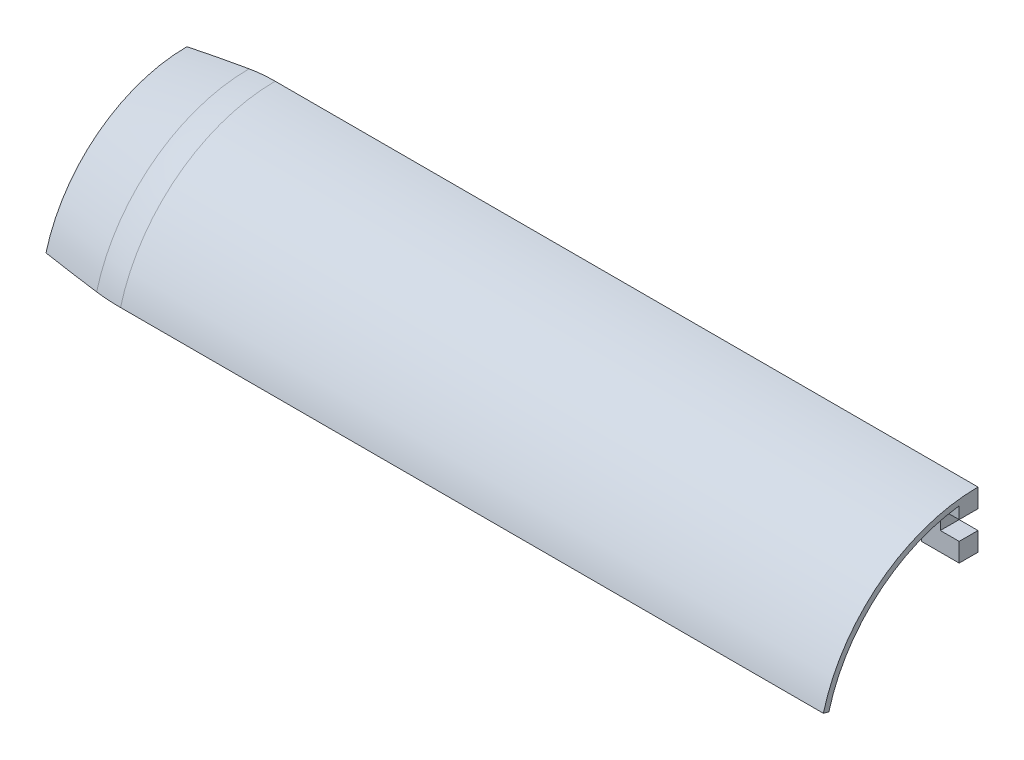
SolidWorks part; units mm, degrees
ref_plane "Front Plane" through (0, 0, 0) normal (0, 0, 1) x (1, 0, 0)
ref_plane "Top Plane" through (0, 0, 0) normal (0, 1, 0) x (1, 0, 0)
ref_plane "Right Plane" through (0, 0, 0) normal (1, 0, 0) x (0, 0, -1)
curve "Curve1"
  spline degree 3 poles (0, 0, 0) (-0.0123, 3.8916, 0) (-0.0274, 8.685, 0) (0.3616, 14.0857, 0) (0.5761, 16.0905, 0) (0.7825, 17.6048, 0) (0.9862, 18.8543, 0) (1.1887, 19.9315, 0) (1.3904, 20.8857, 0) (1.5917, 21.7465, 0) (1.7927, 22.5337, 0) (1.9935, 23.2611, 0) (2.1942, 23.9386, 0) (2.3947, 24.5739, 0) (2.5952, 25.1728, 0) (2.7956, 25.7401, 0) (2.9959, 26.2796, 0) (3.1962, 26.7943, 0) (3.3965, 27.2868, 0) (3.5967, 27.7594, 0) (3.7969, 28.2139, 0) (3.9971, 28.6519, 0) (4.1973, 29.0748, 0) (4.3974, 29.4838, 0) (4.5976, 29.8799, 0) (4.7977, 30.2641, 0) (4.9978, 30.6373, 0) (5.1979, 31.0001, 0) (5.398, 31.3533, 0) (5.5981, 31.6974, 0) (5.7982, 32.033, 0) (5.9983, 32.3606, 0) (6.1984, 32.6807, 0) (6.3985, 32.9935, 0) (6.5985, 33.2996, 0) (6.7986, 33.5993, 0) (6.9986, 33.8929, 0) (7.1987, 34.1806, 0) (7.3987, 34.4628, 0) (7.5988, 34.7397, 0) (7.7988, 35.0115, 0) (7.9989, 35.2785, 0) (8.1989, 35.5408, 0) (8.399, 35.7988, 0) (8.599, 36.0524, 0) (8.799, 36.3019, 0) (8.9991, 36.5476, 0) (9.1991, 36.7894, 0) (9.3991, 37.0275, 0) (9.5992, 37.2622, 0) (9.7992, 37.4934, 0) (9.9992, 37.7214, 0) (10.1992, 37.9461, 0) (10.3993, 38.1679, 0) (10.5993, 38.3866, 0) (10.7993, 38.6025, 0) (10.9993, 38.8156, 0) (11.1993, 39.026, 0) (11.3994, 39.2338, 0) (11.5994, 39.4391, 0) (11.7994, 39.6419, 0) (11.9994, 39.8422, 0) (12.1994, 40.0403, 0) (12.3995, 40.2361, 0) (12.5995, 40.4297, 0) (12.7995, 40.6212, 0) (12.9995, 40.8106, 0) (13.1995, 40.998, 0) (13.3995, 41.1834, 0) (13.5995, 41.3668, 0) (13.7995, 41.5484, 0) (13.9996, 41.7281, 0) (14.1996, 41.9061, 0) (14.3996, 42.0823, 0) (14.5996, 42.2568, 0) (14.7996, 42.4296, 0) (14.9996, 42.6008, 0) (15.1996, 42.7705, 0) (15.3996, 42.9385, 0) (15.5996, 43.1051, 0) (15.7996, 43.2701, 0) (15.9997, 43.4337, 0) (16.1997, 43.5959, 0) (16.3997, 43.7567, 0) (16.5997, 43.9161, 0) (16.7997, 44.0742, 0) (16.9997, 44.2309, 0) (17.1997, 44.3864, 0) (17.3997, 44.5406, 0) (17.5997, 44.6936, 0) (17.7997, 44.8453, 0) (17.9997, 44.9959, 0) (18.1997, 45.1453, 0) (18.3997, 45.2936, 0) (18.5997, 45.4407, 0) (18.7997, 45.5868, 0) (18.9997, 45.7317, 0) (19.1998, 45.8756, 0) (19.3998, 46.0185, 0) (19.5998, 46.1603, 0) (19.7998, 46.3011, 0) (19.9998, 46.4409, 0) (20.1998, 46.5797, 0) (20.3998, 46.7176, 0) (20.5998, 46.8546, 0) (20.7998, 46.9906, 0) (20.9998, 47.1257, 0) (21.1998, 47.2599, 0) (21.3998, 47.3932, 0) (21.5998, 47.5256, 0) (21.7998, 47.6572, 0) (21.9998, 47.788, 0) (22.1998, 47.9179, 0) (22.3998, 48.047, 0) (22.5998, 48.1753, 0) (22.7998, 48.3028, 0) (22.9998, 48.4295, 0) (23.1998, 48.5555, 0) (23.3998, 48.6807, 0) (23.5998, 48.8051, 0) (23.7998, 48.9288, 0) (23.9998, 49.0518, 0) (24.1998, 49.1741, 0) (24.3998, 49.2957, 0) (24.5998, 49.4165, 0) (24.7999, 49.5367, 0) (24.9999, 49.6562, 0) (25.1999, 49.7751, 0) (25.3999, 49.8933, 0) (25.5999, 50.0108, 0) (25.7999, 50.1277, 0) (25.9999, 50.2439, 0) (26.1999, 50.3596, 0) (26.3999, 50.4746, 0) (26.5999, 50.589, 0) (26.7999, 50.7028, 0) (26.9999, 50.8161, 0) (27.1999, 50.9287, 0) (27.3999, 51.0407, 0) (27.5999, 51.1522, 0) (27.7999, 51.2631, 0) (27.9999, 51.3735, 0) (28.1999, 51.4833, 0) (28.3999, 51.5926, 0) (28.5999, 51.7013, 0) (28.7999, 51.8095, 0) (28.9999, 51.9172, 0) (29.1999, 52.0243, 0) (29.3999, 52.131, 0) (29.5999, 52.2371, 0) (29.7999, 52.3428, 0) (29.9999, 52.4479, 0) (30.1999, 52.5526, 0) (30.3999, 52.6567, 0) (30.5999, 52.7604, 0) (30.7999, 52.8636, 0) (30.9999, 52.9664, 0) (31.1999, 53.0687, 0) (31.3999, 53.1705, 0) (31.5999, 53.2719, 0) (31.7999, 53.3728, 0) (31.9999, 53.4733, 0) (32.1999, 53.5733, 0) (32.3999, 53.6729, 0) (32.5999, 53.7721, 0) (32.7999, 53.8709, 0) (32.9999, 53.9692, 0) (33.1999, 54.0671, 0) (33.3999, 54.1646, 0) (33.5999, 54.2617, 0) (33.7999, 54.3584, 0) (33.9999, 54.4547, 0) (34.1999, 54.5506, 0) (34.3999, 54.6461, 0) (34.5999, 54.7412, 0) (34.7999, 54.836, 0) (34.9999, 54.9303, 0) (35.1999, 55.0243, 0) (35.3999, 55.1179, 0) (35.5999, 55.2111, 0) (35.7999, 55.304, 0) (35.9999, 55.3965, 0) (36.1999, 55.4887, 0) (36.3999, 55.5805, 0) (36.5999, 55.6719, 0) (36.7999, 55.763, 0) (36.9999, 55.8537, 0) (37.1999, 55.9441, 0) (37.3999, 56.0342, 0) (37.5999, 56.1239, 0) (37.7999, 56.2133, 0) (37.9999, 56.3024, 0) (38.1999, 56.3911, 0) (38.3999, 56.4795, 0) (38.5999, 56.5676, 0) (38.7999, 56.6554, 0) (38.9999, 56.7428, 0) (39.1999, 56.83, 0) (39.3999, 56.9168, 0) (39.5999, 57.0033, 0) (39.7999, 57.0896, 0) (39.9999, 57.1755, 0) (40.1999, 57.2611, 0) (40.3999, 57.3464, 0) (40.5999, 57.4314, 0) (40.7999, 57.5161, 0) (40.9999, 57.6006, 0) (41.1999, 57.6847, 0) (41.3999, 57.7686, 0) (41.6, 57.8522, 0) (41.8, 57.9355, 0) (42, 58.0185, 0) (42.2, 58.1012, 0) (42.4, 58.1837, 0) (42.6, 58.2659, 0) (42.8, 58.3479, 0) (43, 58.4295, 0) (43.2, 58.5109, 0) (43.4, 58.592, 0) (43.6, 58.6729, 0) (43.8, 58.7535, 0) (44, 58.8339, 0) (44.2, 58.914, 0) (44.4, 58.9938, 0) (44.6, 59.0734, 0) (44.8, 59.1528, 0) (45, 59.2319, 0) (45.2, 59.3107, 0) (45.4, 59.3893, 0) (45.6, 59.4677, 0) (45.8, 59.5458, 0) (46, 59.6237, 0) (46.2, 59.7014, 0) (46.4, 59.7788, 0) (46.6, 59.856, 0) (46.8, 59.9329, 0) (47, 60.0096, 0) (47.2, 60.0861, 0) (47.4, 60.1624, 0) (47.6, 60.2385, 0) (47.8, 60.3143, 0) (48, 60.3899, 0) (48.2, 60.4652, 0) (48.4, 60.5404, 0) (48.6, 60.6153, 0) (48.8, 60.6901, 0) (49, 60.7646, 0) (49.2, 60.8389, 0) (49.4, 60.913, 0) (49.6, 60.9869, 0) (49.8, 61.0605, 0) (50, 61.134, 0) (50.2, 61.2072, 0) (50.4, 61.2803, 0) (50.6, 61.3531, 0) (50.8, 61.4258, 0) (51, 61.4982, 0) (51.2, 61.5705, 0) (51.4, 61.6426, 0) (51.6, 61.7144, 0) (51.8, 61.7861, 0) (52, 61.8575, 0) (52.2, 61.9288, 0) (52.4, 61.9999, 0) (52.6, 62.0708, 0) (52.8, 62.1415, 0) (53, 62.212, 0) (53.2, 62.2824, 0) (53.4, 62.3525, 0) (53.6, 62.4225, 0) (53.8, 62.4923, 0) (54, 62.5619, 0) (54.2, 62.6313, 0) (54.4, 62.7006, 0) (54.6, 62.7696, 0) (54.8, 62.8385, 0) (55, 62.9072, 0) (55.2, 62.9758, 0) (55.4, 63.0441, 0) (55.6, 63.1123, 0) (55.8, 63.1803, 0) (56, 63.2482, 0) (56.2, 63.3159, 0) (56.4, 63.3834, 0) (56.6, 63.4507, 0) (56.8, 63.5179, 0) (57, 63.5849, 0) (57.2, 63.6518, 0) (57.4, 63.7185, 0) (57.6, 63.785, 0) (57.8, 63.8513, 0) (58, 63.9175, 0) (58.2, 63.9836, 0) (58.4, 64.0495, 0) (58.6, 64.1152, 0) (58.8, 64.1808, 0) (59, 64.2462, 0) (59.2, 64.3114, 0) (59.4, 64.3765, 0) (59.6, 64.4415, 0) (59.8, 64.5063, 0) (60, 64.5709, 0) (60.2, 64.6354, 0) (60.4, 64.6998, 0) (60.6, 64.764, 0) (60.8, 64.828, 0) (61, 64.8919, 0) (61.2, 64.9557, 0) (61.4, 65.0193, 0) (61.6, 65.0827, 0) (61.8, 65.1461, 0) (62, 65.2092, 0) (62.2, 65.2723, 0) (62.4, 65.3352, 0) (62.6, 65.3979, 0) (62.8, 65.4605, 0) (63, 65.523, 0) (63.2, 65.5853, 0) (63.4, 65.6475, 0) (63.6, 65.7096, 0) (63.8, 65.7715, 0) (64, 65.8333, 0) (64.2, 65.895, 0) (64.4, 65.9565, 0) (64.6, 66.0179, 0) (64.8, 66.0791, 0) (65, 66.1402, 0) (65.2, 66.2012, 0) (65.4, 66.2621, 0) (65.6, 66.3228, 0) (65.8, 66.3834, 0) (66, 66.4439, 0) (66.2, 66.5042, 0) (66.4, 66.5644, 0) (66.6, 66.6245, 0) (66.8, 66.6845, 0) (67, 66.7443, 0) (67.2, 66.804, 0) (67.4, 66.8636, 0) (67.6, 66.923, 0) (67.8, 66.9824, 0) (68, 67.0416, 0) (68.2, 67.1007, 0) (68.4, 67.1597, 0) (68.6, 67.2185, 0) (68.8, 67.2772, 0) (69, 67.3359, 0) (69.2, 67.3943, 0) (69.4, 67.4527, 0) (69.6, 67.511, 0) (69.8, 67.5691, 0) (70, 67.6271, 0) (70.2, 67.6851, 0) (70.4, 67.7428, 0) (70.6, 67.8005, 0) (70.8, 67.8581, 0) (71, 67.9155, 0) (71.2, 67.9729, 0) (71.4, 68.0301, 0) (71.6, 68.0872, 0) (71.8, 68.1442, 0) (72, 68.2011, 0) (72.2, 68.2579, 0) (72.4, 68.3145, 0) (72.6, 68.3711, 0) (72.8, 68.4276, 0) (73, 68.4839, 0) (73.2, 68.5401, 0) (73.4, 68.5963, 0) (73.6, 68.6523, 0) (73.8, 68.7082, 0) (74, 68.764, 0) (74.2, 68.8197, 0) (74.4, 68.8753, 0) (74.6, 68.9308, 0) (74.8, 68.9862, 0) (75, 69.0415, 0) (75.2, 69.0966, 0) (75.4, 69.1517, 0) (75.6, 69.2067, 0) (75.8, 69.2616, 0) (76, 69.3164, 0) (76.2, 69.371, 0) (76.4, 69.4256, 0) (76.6, 69.4801, 0) (76.8, 69.5344, 0) (77, 69.5887, 0) (77.2, 69.6429, 0) (77.4, 69.697, 0) (77.6, 69.751, 0) (77.8, 69.8048, 0) (78, 69.8586, 0) (78.2, 69.9123, 0) (78.4, 69.9659, 0) (78.6, 70.0194, 0) (78.8, 70.0728, 0) (79, 70.1261, 0) (79.2, 70.1793, 0) (79.4, 70.2324, 0) (79.6, 70.2855, 0) (79.8, 70.3384, 0) (80, 70.3912, 0) (80.2, 70.444, 0) (80.4, 70.4966, 0) (80.6, 70.5492, 0) (80.8, 70.6017, 0) (81, 70.6541, 0) (81.2, 70.7064, 0) (81.4, 70.7586, 0) (81.6, 70.8107, 0) (81.8, 70.8627, 0) (82, 70.9146, 0) (82.2, 70.9665, 0) (82.4, 71.0182, 0) (82.6, 71.0699, 0) (82.8, 71.1215, 0) (83, 71.173, 0) (83.2, 71.2244, 0) (83.4, 71.2757, 0) (83.6, 71.3269, 0) (83.8, 71.3781, 0) (84, 71.4291, 0) (84.2, 71.4801, 0) (84.4, 71.531, 0) (84.6, 71.5818, 0) (84.8, 71.6325, 0) (85, 71.6832, 0) (85.2, 71.7337, 0) (85.4, 71.7842, 0) (85.6, 71.8346, 0) (85.8, 71.8849, 0) (86, 71.9351, 0) (86.2, 71.9853, 0) (86.4, 72.0354, 0) (86.6, 72.0853, 0) (86.8, 72.1352, 0) (87, 72.1851, 0) (87.2, 72.2348, 0) (87.4, 72.2845, 0) (87.6, 72.3341, 0) (87.8, 72.3836, 0) (88, 72.433, 0) (88.2, 72.4823, 0) (88.4, 72.5316, 0) (88.6, 72.5808, 0) (88.8, 72.6299, 0) (89, 72.6789, 0) (89.2, 72.7279, 0) (89.4, 72.7768, 0) (89.6, 72.8256, 0) (89.8, 72.8743, 0) (90, 72.923, 0) (90.2, 72.9716, 0) (90.4, 73.0201, 0) (90.6, 73.0685, 0) (90.8, 73.1168, 0) (91, 73.1651, 0) (91.2, 73.2133, 0) (91.4, 73.2614, 0) (91.6, 73.3095, 0) (91.8, 73.3575, 0) (92, 73.4054, 0) (92.2, 73.4532, 0) (92.4, 73.501, 0) (92.6, 73.5487, 0) (92.8, 73.5963, 0) (93, 73.6439, 0) (93.2, 73.6913, 0) (93.4, 73.7387, 0) (93.6, 73.7861, 0) (93.8, 73.8333, 0) (94, 73.8805, 0) (94.2, 73.9276, 0) (94.4, 73.9747, 0) (94.6, 74.0217, 0) (94.8, 74.0686, 0) (95, 74.1154, 0) (95.2, 74.1622, 0) (95.4, 74.2089, 0) (95.6, 74.2556, 0) (95.8, 74.3021, 0) (96, 74.3486, 0) (96.2, 74.3951, 0) (96.4, 74.4414, 0) (96.6, 74.4877, 0) (96.8, 74.534, 0) (97, 74.5801, 0) (97.2, 74.6262, 0) (97.4, 74.6723, 0) (97.6, 74.7182, 0) (97.8, 74.7641, 0) (98, 74.81, 0) (98.2, 74.8557, 0) (98.4, 74.9014, 0) (98.6, 74.9471, 0) (98.8, 74.9926, 0) (99, 75.0382, 0) (99.2, 75.0836, 0) (99.4, 75.129, 0) (99.6, 75.1743, 0) (99.8, 75.2196, 0) (100, 75.2647, 0) (100.2, 75.3099, 0) (100.4, 75.3549, 0) (100.6, 75.3999, 0) (100.8, 75.4449, 0) (101, 75.4898, 0) (101.2, 75.5346, 0) (101.4, 75.5793, 0) (101.6, 75.624, 0) (101.8, 75.6686, 0) (102, 75.7132, 0) (102.2, 75.7577, 0) (102.4, 75.8022, 0) (102.6, 75.8465, 0) (102.8, 75.8909, 0) (103, 75.9351, 0) (103.2, 75.9793, 0) (103.4, 76.0235, 0) (103.6, 76.0676, 0) (103.8, 76.1116, 0) (104, 76.1556, 0) (104.2, 76.1995, 0) (104.4, 76.2433, 0) (104.6, 76.2871, 0) (104.8, 76.3308, 0) (105, 76.3745, 0) (105.2, 76.4181, 0) (105.4, 76.4617, 0) (105.6, 76.5052, 0) (105.8, 76.5486, 0) (106, 76.592, 0) (106.2, 76.6353, 0) (106.4, 76.6786, 0) (106.6, 76.7218, 0) (106.8, 76.7649, 0) (107, 76.808, 0) (107.2, 76.8511, 0) (107.4, 76.8941, 0) (107.6, 76.937, 0) (107.8, 76.9799, 0) (108, 77.0227, 0) (108.2, 77.0655, 0) (108.4, 77.1082, 0) (108.6, 77.1508, 0) (108.8, 77.1934, 0) (109, 77.236, 0) (109.2, 77.2784, 0) (109.4, 77.3209, 0) (109.6, 77.3633, 0) (109.8, 77.4056, 0) (110, 77.4479, 0) (110.2, 77.4901, 0) (110.4, 77.5322, 0) (110.6, 77.5743, 0) (110.8, 77.6164, 0) (111, 77.6584, 0) (111.2, 77.7004, 0) (111.4, 77.7423, 0) (111.6, 77.7841, 0) (111.8, 77.8259, 0) (112, 77.8676, 0) (112.2, 77.9093, 0) (112.4, 77.951, 0) (112.6, 77.9925, 0) (112.8, 78.0341, 0) (113, 78.0756, 0) (113.2, 78.117, 0) (113.4, 78.1584, 0) (113.6, 78.1997, 0) (113.8, 78.241, 0) (114, 78.2822, 0) (114.2, 78.3234, 0) (114.4, 78.3645, 0) (114.6, 78.4056, 0) (114.8, 78.4466, 0) (115, 78.4876, 0) (115.2, 78.5285, 0) (115.4, 78.5694, 0) (115.6, 78.6102, 0) (115.8, 78.651, 0) (116, 78.6917, 0) (116.2, 78.7324, 0) (116.4, 78.773, 0) (116.6, 78.8136, 0) (116.8, 78.8541, 0) (117, 78.8946, 0) (117.2, 78.935, 0) (117.4, 78.9754, 0) (117.6, 79.0158, 0) (117.8, 79.0561, 0) (118, 79.0963, 0) (118.2, 79.1365, 0) (118.4, 79.1766, 0) (118.6, 79.2167, 0) (118.8, 79.2568, 0) (119, 79.2968, 0) (119.2, 79.3368, 0) (119.4, 79.3767, 0) (119.6, 79.4165, 0) (119.8, 79.4564, 0) (120, 79.4961, 0) (120.2, 79.5358, 0) (120.4, 79.5755, 0) (120.6, 79.6152, 0) (120.8, 79.6547, 0) (121, 79.6943, 0) (121.2, 79.7338, 0) (121.4, 79.7732, 0) (121.6, 79.8126, 0) (121.8, 79.852, 0) (122, 79.8913, 0) (122.2, 79.9306, 0) (122.4, 79.9698, 0) (122.6, 80.009, 0) (122.8, 80.0481, 0) (123, 80.0872, 0) (123.2, 80.1262, 0) (123.4, 80.1652, 0) (123.6, 80.2042, 0) (123.8, 80.2431, 0) (124, 80.282, 0) (124.2, 80.3208, 0) (124.4, 80.3596, 0) (124.6, 80.3983, 0) (124.8, 80.437, 0) (125, 80.4757, 0) (125.2, 80.5143, 0) (125.4, 80.5528, 0) (125.6, 80.5914, 0) (125.8, 80.6298, 0) (126, 80.6683, 0) (126.2, 80.7067, 0) (126.4, 80.745, 0) (126.6, 80.7833, 0) (126.8, 80.8216, 0) (127, 80.8598, 0) (127.2, 80.898, 0) (127.4, 80.9361, 0) (127.6, 80.9742, 0) (127.8, 81.0123, 0) (128, 81.0503, 0) (128.2, 81.0883, 0) (128.4, 81.1262, 0) (128.6, 81.1641, 0) (128.8, 81.2019, 0) (129, 81.2397, 0) (129.2, 81.2775, 0) (129.4, 81.3152, 0) (129.6, 81.3529, 0) (129.8, 81.3906, 0) (130, 81.4282, 0) (130.2, 81.4657, 0) (130.4, 81.5032, 0) (130.6, 81.5407, 0) (130.8, 81.5782, 0) (131, 81.6156, 0) (131.2, 81.6529, 0) (131.4, 81.6902, 0) (131.6, 81.7275, 0) (131.8, 81.7648, 0) (132, 81.802, 0) (132.2, 81.8391, 0) (132.4, 81.8763, 0) (132.6, 81.9133, 0) (132.8, 81.9504, 0) (133, 81.9874, 0) (133.2, 82.0244, 0) (133.4, 82.0613, 0) (133.6, 82.0982, 0) (133.8, 82.135, 0) (134, 82.1718, 0) (134.2, 82.2086, 0) (134.4, 82.2454, 0) (134.6, 82.282, 0) (134.8, 82.3187, 0) (135, 82.3553, 0) (135.2, 82.3919, 0) (135.4, 82.4285, 0) (135.6, 82.465, 0) (135.8, 82.5014, 0) (136, 82.5379, 0) (136.2, 82.5743, 0) (136.4, 82.6106, 0) (136.6, 82.6469, 0) (136.8, 82.6832, 0) (137, 82.7195, 0) (137.2, 82.7557, 0) (137.4, 82.7919, 0) (137.6, 82.828, 0) (137.8, 82.8641, 0) (138, 82.9001, 0) (138.2, 82.9362, 0) (138.4, 82.9722, 0) (138.6, 83.0081, 0) (138.8, 83.044, 0) (139, 83.0799, 0) (139.2, 83.1158, 0) (139.4, 83.1516, 0) (139.6, 83.1873, 0) (139.8, 83.2231, 0) (140, 83.2588, 0) (140.2, 83.2944, 0) (140.4, 83.3301, 0) (140.6, 83.3657, 0) (140.8, 83.4012, 0) (141, 83.4367, 0) (141.2, 83.4722, 0) (141.4, 83.5077, 0) (141.6, 83.5431, 0) (141.8, 83.5785, 0) (142, 83.6138, 0) (142.2, 83.6491, 0) (142.4, 83.6844, 0) (142.6, 83.7197, 0) (142.8, 83.7549, 0) (143, 83.79, 0) (143.2, 83.8252, 0) (143.4, 83.8603, 0) (143.6, 83.8954, 0) (143.8, 83.9304, 0) (144, 83.9654, 0) (144.2, 84.0004, 0) (144.4, 84.0353, 0) (144.6, 84.0702, 0) (144.8, 84.1051, 0) (145, 84.1399, 0) (145.2, 84.1747, 0) (145.4, 84.2095, 0) (145.6, 84.2442, 0) (145.8, 84.2789, 0) (146, 84.3136, 0) (146.2, 84.3482, 0) (146.4, 84.3828, 0) (146.6, 84.4174, 0) (146.8, 84.4519, 0) (147, 84.4864, 0) (147.2, 84.5209, 0) (147.4, 84.5553, 0) (147.6, 84.5897, 0) (147.8, 84.6241, 0) (148, 84.6584, 0) (148.2, 84.6927, 0) (148.4, 84.727, 0) (148.6, 84.7612, 0) (148.8, 84.7954, 0) (149, 84.8296, 0) (149.2, 84.8638, 0) (149.4, 84.8979, 0) (149.6, 84.9319, 0) (149.8, 84.966, 0) (149.9333, 84.9887, 0) (150, 85, 0) knots 0 0 0 0 0.061462 0.075706 0.085548 0.093322 0.099856 0.105554 0.110643 0.115268 0.119525 0.123482 0.127192 0.130691 0.13401 0.137173 0.140199 0.143104 0.145901 0.148602 0.151215 0.15375 0.156213 0.158609 0.160946 0.163227 0.165456 0.167638 0.169775 0.171871 0.173928 0.17595 0.177937 0.179893 0.181819 0.183716 0.185587 0.187433 0.189255 0.191054 0.192831 0.194589 0.196326 0.198045 0.199747 0.201431 0.2031 0.204753 0.206391 0.208015 0.209626 0.211223 0.212808 0.214381 0.215942 0.217493 0.219032 0.220561 0.22208 0.22359 0.225091 0.226582 0.228065 0.229539 0.231006 0.232464 0.233915 0.235359 0.236795 0.238225 0.239648 0.241065 0.242475 0.243879 0.245277 0.24667 0.248057 0.249438 0.250814 0.252185 0.253551 0.254913 0.256269 0.257621 0.258968 0.260311 0.26165 0.262984 0.264315 0.265641 0.266964 0.268282 0.269598 0.270909 0.272217 0.273522 0.274823 0.276121 0.277416 0.278707 0.279996 0.281281 0.282564 0.283843 0.28512 0.286394 0.287666 0.288935 0.290201 0.291465 0.292726 0.293985 0.295241 0.296495 0.297747 0.298996 0.300243 0.301489 0.302732 0.303972 0.305211 0.306448 0.307683 0.308916 0.310147 0.311376 0.312604 0.313829 0.315053 0.316275 0.317495 0.318714 0.319931 0.321147 0.32236 0.323573 0.324783 0.325993 0.3272 0.328406 0.329611 0.330815 0.332017 0.333217 0.334416 0.335614 0.336811 0.338006 0.3392 0.340393 0.341584 0.342775 0.343964 0.345152 0.346339 0.347524 0.348709 0.349892 0.351074 0.352256 0.353436 0.354615 0.355793 0.35697 0.358146 0.359321 0.360495 0.361668 0.36284 0.364011 0.365182 0.366351 0.36752 0.368687 0.369854 0.37102 0.372185 0.373349 0.374512 0.375674 0.376836 0.377997 0.379157 0.380316 0.381475 0.382632 0.383789 0.384946 0.386101 0.387256 0.38841 0.389563 0.390716 0.391868 0.393019 0.39417 0.39532 0.396469 0.397618 0.398766 0.399913 0.40106 0.402206 0.403351 0.404496 0.40564 0.406784 0.407927 0.409069 0.410211 0.411353 0.412493 0.413633 0.414773 0.415912 0.417051 0.418189 0.419326 0.420463 0.4216 0.422736 0.423871 0.425006 0.426141 0.427275 0.428408 0.429541 0.430674 0.431806 0.432937 0.434068 0.435199 0.436329 0.437459 0.438588 0.439717 0.440846 0.441974 0.443101 0.444229 0.445355 0.446482 0.447608 0.448733 0.449858 0.450983 0.452107 0.453231 0.454355 0.455478 0.456601 0.457723 0.458845 0.459967 0.461088 0.462209 0.46333 0.46445 0.46557 0.46669 0.467809 0.468928 0.470046 0.471164 0.472282 0.4734 0.474517 0.475634 0.47675 0.477866 0.478982 0.480098 0.481213 0.482328 0.483443 0.484557 0.485671 0.486785 0.487898 0.489011 0.490124 0.491237 0.492349 0.493461 0.494573 0.495684 0.496796 0.497906 0.499017 0.500127 0.501237 0.502347 0.503457 0.504566 0.505675 0.506784 0.507892 0.509001 0.510109 0.511216 0.512324 0.513431 0.514538 0.515645 0.516752 0.517858 0.518964 0.52007 0.521175 0.522281 0.523386 0.524491 0.525595 0.5267 0.527804 0.528908 0.530012 0.531116 0.532219 0.533322 0.534425 0.535528 0.53663 0.537733 0.538835 0.539937 0.541038 0.54214 0.543241 0.544342 0.545443 0.546544 0.547644 0.548745 0.549845 0.550945 0.552044 0.553144 0.554243 0.555342 0.556441 0.55754 0.558639 0.559737 0.560836 0.561934 0.563032 0.564129 0.565227 0.566324 0.567421 0.568518 0.569615 0.570712 0.571809 0.572905 0.574001 0.575097 0.576193 0.577289 0.578384 0.57948 0.580575 0.58167 0.582765 0.58386 0.584954 0.586049 0.587143 0.588237 0.589331 0.590425 0.591519 0.592612 0.593706 0.594799 0.595892 0.596985 0.598078 0.59917 0.600263 0.601355 0.602448 0.60354 0.604632 0.605724 0.606815 0.607907 0.608998 0.61009 0.611181 0.612272 0.613363 0.614453 0.615544 0.616635 0.617725 0.618815 0.619905 0.620995 0.622085 0.623175 0.624265 0.625354 0.626443 0.627533 0.628622 0.629711 0.6308 0.631888 0.632977 0.634066 0.635154 0.636242 0.637331 0.638419 0.639507 0.640594 0.641682 0.64277 0.643857 0.644945 0.646032 0.647119 0.648206 0.649293 0.65038 0.651467 0.652553 0.65364 0.654726 0.655813 0.656899 0.657985 0.659071 0.660157 0.661243 0.662328 0.663414 0.664499 0.665585 0.66667 0.667755 0.66884 0.669925 0.67101 0.672095 0.67318 0.674264 0.675349 0.676433 0.677518 0.678602 0.679686 0.68077 0.681854 0.682938 0.684022 0.685105 0.686189 0.687272 0.688356 0.689439 0.690522 0.691605 0.692688 0.693771 0.694854 0.695937 0.69702 0.698102 0.699185 0.700267 0.70135 0.702432 0.703514 0.704596 0.705678 0.70676 0.707842 0.708924 0.710006 0.711087 0.712169 0.71325 0.714332 0.715413 0.716494 0.717575 0.718656 0.719737 0.720818 0.721899 0.72298 0.724061 0.725141 0.726222 0.727302 0.728382 0.729463 0.730543 0.731623 0.732703 0.733783 0.734863 0.735943 0.737023 0.738103 0.739182 0.740262 0.741341 0.742421 0.7435 0.744579 0.745659 0.746738 0.747817 0.748896 0.749975 0.751054 0.752133 0.753211 0.75429 0.755369 0.756447 0.757526 0.758604 0.759682 0.760761 0.761839 0.762917 0.763995 0.765073 0.766151 0.767229 0.768307 0.769385 0.770462 0.77154 0.772618 0.773695 0.774773 0.77585 0.776927 0.778005 0.779082 0.780159 0.781236 0.782313 0.78339 0.784467 0.785544 0.786621 0.787698 0.788774 0.789851 0.790928 0.792004 0.793081 0.794157 0.795233 0.79631 0.797386 0.798462 0.799538 0.800614 0.80169 0.802766 0.803842 0.804918 0.805994 0.80707 0.808145 0.809221 0.810296 0.811372 0.812447 0.813523 0.814598 0.815674 0.816749 0.817824 0.818899 0.819974 0.821049 0.822124 0.823199 0.824274 0.825349 0.826424 0.827499 0.828573 0.829648 0.830723 0.831797 0.832872 0.833946 0.835021 0.836095 0.837169 0.838244 0.839318 0.840392 0.841466 0.84254 0.843614 0.844688 0.845762 0.846836 0.84791 0.848984 0.850058 0.851131 0.852205 0.853279 0.854352 0.855426 0.856499 0.857573 0.858646 0.859719 0.860793 0.861866 0.862939 0.864012 0.865085 0.866159 0.867232 0.868305 0.869378 0.87045 0.871523 0.872596 0.873669 0.874742 0.875814 0.876887 0.87796 0.879032 0.880105 0.881177 0.88225 0.883322 0.884395 0.885467 0.886539 0.887611 0.888684 0.889756 0.890828 0.8919 0.892972 0.894044 0.895116 0.896188 0.89726 0.898332 0.899404 0.900475 0.901547 0.902619 0.90369 0.904762 0.905834 0.906905 0.907977 0.909048 0.91012 0.911191 0.912262 0.913334 0.914405 0.915476 0.916548 0.917619 0.91869 0.919761 0.920832 0.921903 0.922974 0.924045 0.925116 0.926187 0.927258 0.928329 0.929399 0.93047 0.931541 0.932612 0.933682 0.934753 0.935823 0.936894 0.937965 0.939035 0.940105 0.941176 0.942246 0.943317 0.944387 0.945457 0.946527 0.947598 0.948668 0.949738 0.950808 0.951878 0.952948 0.954018 0.955088 0.956158 0.957228 0.958298 0.959368 0.960438 0.961508 0.962577 0.963647 0.964717 0.965786 0.966856 0.967926 0.968995 0.970065 0.971134 0.972204 0.973273 0.974343 0.975412 0.976481 0.977551 0.97862 0.979689 0.980759 0.981828 0.982897 0.983966 0.985035 0.986104 0.987173 0.988242 0.989311 0.99038 0.991449 0.992518 0.993587 0.994656 0.995725 0.996794 0.997863 0.998931 1 1 1 1
sketch "Sketch1" plane through (0, 0, 0) normal (0, 0, 1) x (1, 0, 0)
  line L0 (0, 0) -> (3, 0)
  line L1 (3, 0.0095) -> (3, 0)
  line L3 (150, 85) -> (530, 85)
  line L4 (150, 81.9569) -> (530, 81.9569)
  line L5 (530, 81.9569) -> (530, 85)
  line L6 (0, 0) -> (686.3935, 0) construction
  spline S0 degree 3 poles (-4988.3045, -127.8298) (181.331, -218.097) (-7.7458, -98.4721) (0.3616, 14.0857) (0.5761, 16.0905) (0.7825, 17.6048) (0.9862, 18.8543) (1.1887, 19.9315) (1.3904, 20.8857) (1.5917, 21.7465) (1.7927, 22.5337) (1.9935, 23.2611) (2.2538, 24.14) (2.5806, 25.1462) (2.9836, 26.2595) (3.3859, 27.2713) (3.7877, 28.2016) (4.1891, 29.0648) (4.5903, 29.8717) (5.0533, 30.7478) (5.5832, 31.6835) (6.1854, 32.6697) (6.7872, 33.5906) (7.4515, 34.5461) (8.1828, 35.531) (8.9851, 36.54) (9.8503, 37.5625) (10.7826, 38.5957) (11.785, 39.6369) (12.851, 40.6804) (13.984, 41.7246) (15.1862, 42.7682) (16.388, 43.7553) (17.6544, 44.7435) (18.9876, 45.7315) (20.3892, 46.7179) (21.7905, 47.6579) (23.2571, 48.5984) (24.7904, 49.5382) (26.3916, 50.4762) (28.0583, 51.4122) (29.7917, 52.3451) (31.5927, 53.2742) (33.4594, 54.1996) (35.3929, 55.1207) (37.4597, 56.0672) (39.5933, 57.0066) (41.8602, 57.9666) (44.1937, 58.9175) (46.6606, 59.8853) (49.2604, 60.8677) (51.994, 61.8617) (54.861, 62.8656) (57.7946, 63.8556) (60.8615, 64.8536) (64.0615, 65.8584) (67.4615, 66.8882) (70.9951, 67.9202) (74.6621, 68.9539) (78.4621, 69.9886) (82.4622, 71.0404) (86.6623, 72.1071) (91.0624, 73.1864) (95.6625, 74.2764) (100.4626, 75.3753) (105.4628, 76.4816) (110.6629, 77.5938) (116.063, 78.7107) (121.6632, 79.8312) (127.5299, 80.9671) (133.6633, 82.1162) (140.0634, 83.2764) (145.1985, 84.1774) (148.3332, 84.7158) (149.3333, 84.8865) (149.6, 84.9319) (210.4736, 95.2955) (272.2046, 100.2158) (-505.3505, 5038.0754) knots -1.697374 -1.697374 -1.697374 -1.697374 0.061462 0.075706 0.085548 0.093322 0.099856 0.105554 0.110643 0.115268 0.119525 0.123482 0.127192 0.13401 0.140199 0.145901 0.151215 0.156213 0.160946 0.165456 0.171871 0.177937 0.183716 0.189255 0.196326 0.2031 0.209626 0.217493 0.225091 0.232464 0.241065 0.249438 0.257621 0.265641 0.274823 0.283843 0.292726 0.301489 0.311376 0.321147 0.330815 0.341584 0.352256 0.36284 0.374512 0.386101 0.398766 0.411353 0.425006 0.438588 0.453231 0.468928 0.484557 0.501237 0.517858 0.535528 0.554243 0.574001 0.593706 0.614453 0.636242 0.659071 0.682938 0.707842 0.733783 0.760761 0.788774 0.817824 0.84791 0.879032 0.912262 0.946527 0.981828 0.994656 0.996794 0.997863 0.998931 1.972677 1.972677 1.972677 1.972677 only from (0, 0) to (150, 85) construction
  spline S1 degree 3 poles (0, 0) (-0.0123, 3.8916) (-0.0274, 8.685) (0.3616, 14.0857) (0.5761, 16.0905) (0.7825, 17.6048) (0.9862, 18.8543) (1.1887, 19.9315) (1.3904, 20.8857) (1.5917, 21.7465) (1.7927, 22.5337) (1.9935, 23.2611) (2.2538, 24.14) (2.5806, 25.1462) (2.9836, 26.2595) (3.3859, 27.2713) (3.7877, 28.2016) (4.1891, 29.0648) (4.5903, 29.8717) (5.0533, 30.7478) (5.5832, 31.6835) (6.1854, 32.6697) (6.7872, 33.5906) (7.4515, 34.5461) (8.1828, 35.531) (8.9851, 36.54) (9.8503, 37.5625) (10.7826, 38.5957) (11.785, 39.6369) (12.851, 40.6804) (13.984, 41.7246) (15.1862, 42.7682) (16.388, 43.7553) (17.6544, 44.7435) (18.9876, 45.7315) (20.3892, 46.7179) (21.7905, 47.6579) (23.2571, 48.5984) (24.7904, 49.5382) (26.3916, 50.4762) (28.0583, 51.4122) (29.7917, 52.3451) (31.5927, 53.2742) (33.4594, 54.1996) (35.3929, 55.1207) (37.4597, 56.0672) (39.5933, 57.0066) (41.8602, 57.9666) (44.1937, 58.9175) (46.6606, 59.8853) (49.2604, 60.8677) (51.994, 61.8617) (54.861, 62.8656) (57.7946, 63.8556) (60.8615, 64.8536) (64.0615, 65.8584) (67.4615, 66.8882) (70.9951, 67.9202) (74.6621, 68.9539) (78.4621, 69.9886) (82.4622, 71.0404) (86.6623, 72.1071) (91.0624, 73.1864) (95.6625, 74.2764) (100.4626, 75.3753) (105.4628, 76.4816) (110.6629, 77.5938) (116.063, 78.7107) (121.6632, 79.8312) (127.5299, 80.9671) (133.6633, 82.1162) (140.0634, 83.2764) (145.1985, 84.1774) (148.3332, 84.7158) (149.4, 84.8979) (149.7333, 84.9547) (149.9333, 84.9887) (150, 85) knots 0 0 0 0 0.061462 0.075706 0.085548 0.093322 0.099856 0.105554 0.110643 0.115268 0.119525 0.123482 0.127192 0.13401 0.140199 0.145901 0.151215 0.156213 0.160946 0.165456 0.171871 0.177937 0.183716 0.189255 0.196326 0.2031 0.209626 0.217493 0.225091 0.232464 0.241065 0.249438 0.257621 0.265641 0.274823 0.283843 0.292726 0.301489 0.311376 0.321147 0.330815 0.341584 0.352256 0.36284 0.374512 0.386101 0.398766 0.411353 0.425006 0.438588 0.453231 0.468928 0.484557 0.501237 0.517858 0.535528 0.554243 0.574001 0.593706 0.614453 0.636242 0.659071 0.682938 0.707842 0.733783 0.760761 0.788774 0.817824 0.84791 0.879032 0.912262 0.946527 0.981828 0.994656 0.996794 0.998931 1 1 1 1
  spline S2 degree 1 poles (3, 0.0095) (150.5029, 82.0425) knots 0 0 1 1 construction
  spline S3 degree 3 poles (3, 0.0095) (2.9938, 1.972) (2.982, 5.9191) (3.1454, 11.707) (3.6738, 17.3485) (4.827, 22.758) (6.7674, 27.8489) (10.4623, 34.1061) (16.9323, 40.8089) (26.3776, 47.2586) (36.673, 52.5723) (47.4414, 57.081) (62.1775, 62.3104) (81.0422, 67.7575) (104.0182, 73.2189) (126.9821, 77.894) (142.3896, 80.66) (150.1676, 81.9854) (150.3773, 82.0211) (150.5029, 82.0425) knots 0 0 0 0 0.03125 0.0625 0.09375 0.125 0.15625 0.1875 0.25 0.3125 0.375 0.4375 0.5 0.625 0.75 0.875 0.996634 0.99798 1 1 1 1 only from (3, 0.0095) to (150, 81.9569)
  dimension "D2" = 380
  dimension "D1" = 3
revolve "Revolve1" add sketch "Sketch1" angle 75 about L6
fillet "Fillet1" radius 80 1 edges at (150, 65.0207, 49.8922)
fillet "Fillet2" radius 80 1 edges at (150, 67.435, 51.7447)
sketch "Sketch3" plane through (0, 0, 0) normal (0, 1, 0) x (1, 0, 0)
  line L1 (-110, -104.4531) -> (110, -104.4531)
  line L2 (-110, -104.4531) -> (-110, 104.4531)
  line L3 (-110, 104.4531) -> (110, 104.4531)
  line L4 (110, -104.4531) -> (110, 104.4531)
  line L5 (-110, -104.4531) -> (110, 104.4531) construction
  line L6 (-110, 104.4531) -> (110, -104.4531) construction
  point P0 (0, 0)
  dimension "D1" = 110
extrude "Cut-Extrude3" cut sketch "Sketch3" along normal blind 159
sketch "Sketch5" plane through (530, 0, 0) normal (1, 0, 0) x (0, 0, -1)
  line L2 (0, 85) -> (0, 55)
  line L3 (0, 55) -> (-10, 55)
  line L4 (-10, 84.4097) -> (-10, 55)
  arc A0 (0, 85) -> (-10, 84.4097) centre (0, 0) ccw
  arc A1 (0, 85) -> (-82.1037, 21.9996) centre (0, 0) ccw construction
  dimension "D1" = 30
  dimension "D2" = 10
extrude "Boss-Extrude1" add sketch "Sketch5" against normal blind 20
sketch "Sketch6" plane through (530, 0, 0) normal (1, 0, 0) x (0, 0, -1)
  line L0 (0, 0) -> (0, 85) construction
  line L1 (0, 65) -> (-10, 65)
  line L2 (0, 65) -> (0, 75)
  line L3 (0, 75) -> (-10, 75)
  line L4 (-10, 65) -> (-10, 75)
  line L5 (-10, 81.3445) -> (-10, 55) construction
  line L6 (-10, 55) -> (0, 55) construction
  dimension "D1" = 10
  dimension "D2" = 10
extrude "Cut-Extrude4" cut sketch "Sketch6" against normal blind 10
